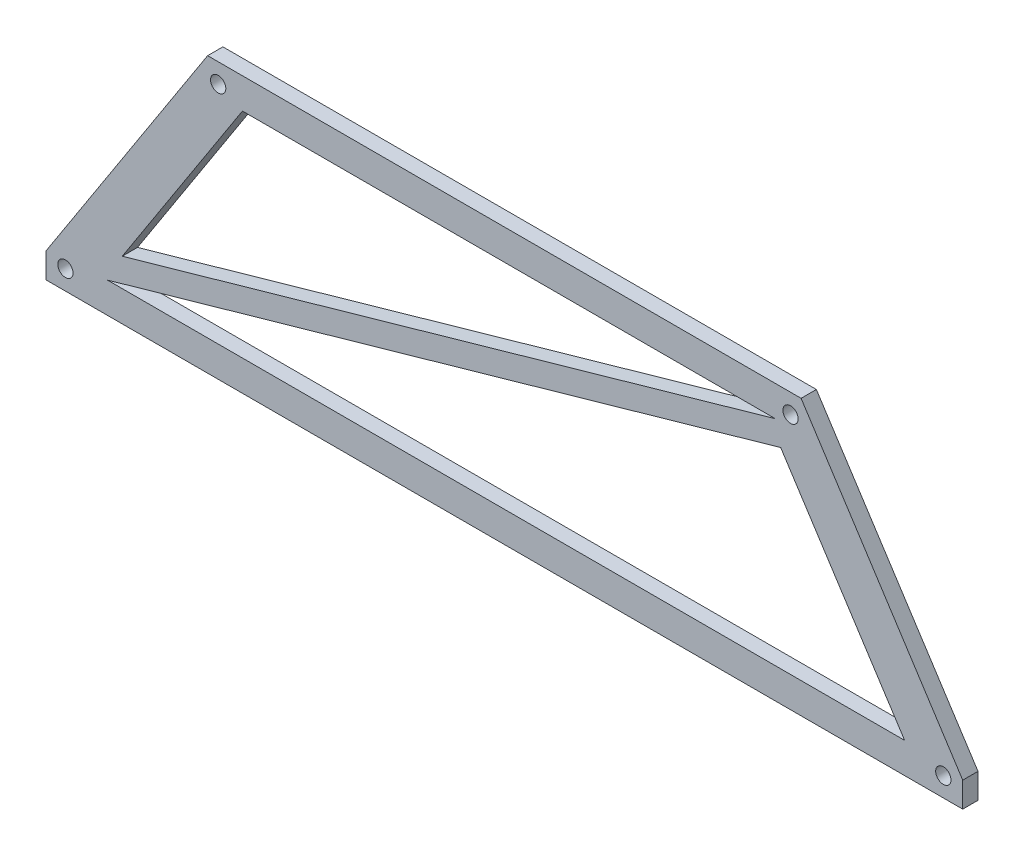
SolidWorks part; units mm, degrees
ref_plane "Front Plane" through (0, 0, 0) normal (0, 0, 1) x (1, 0, 0)
ref_plane "Top Plane" through (0, 0, 0) normal (0, 1, 0) x (1, 0, 0)
ref_plane "Right Plane" through (0, 0, 0) normal (1, 0, 0) x (0, 0, -1)
sketch "Sketch1" plane through (0, 0, 0) normal (0, 0, 1) x (1, 0, 0)
  line L2 (300, -109.2652) -> (300, -92.8158)
  line L3 (194.2105, 70.7348) -> (-194.2105, 70.7348)
  line L4 (-300, -109.2652) -> (-300, -92.8158)
  line L5 (300, -109.2652) -> (-194.2105, 70.7348) construction
  line L6 (194.2105, 70.7348) -> (-300, -109.2652) construction
  line L9 (300, -109.2652) -> (-300, -109.2652)
  line L10 (0, -55) -> (0, 55) construction
  line L11 (-194.2105, 70.7348) -> (-300, -92.8158)
  line L12 (194.2105, 70.7348) -> (300, -92.8158)
  circle A0 centre (-187.3, 58.0348) radius 5
  circle A1 centre (-287.3, -96.5652) radius 5
  circle A2 centre (287.3, -96.5652) radius 5
  circle A3 centre (187.3, 58.0348) radius 5
  point P0 (0, 0)
  dimension "D7" = 10
  dimension "D2" = 12.7
  dimension "D3" = 12.7
  dimension "D4" = 600
  dimension "D5" = 12.7
  dimension "D8" = 112.7
  dimension "D9" = 154.6
  dimension "D10" = 12.7
  dimension "D11" = 12.7
extrude "Boss-Extrude1" add sketch "Sketch1" along normal blind 10
sketch "Sketch2" plane through (0, 0, 10) normal (0, 0, 1) x (1, 0, 0)
  line L0 (180.8634, 36.1325) -> (261.9745, -89.2652)
  line L1 (261.9745, -89.2652) -> (-259.82, -89.2652)
  line L2 (-259.82, -89.2652) -> (180.8634, 36.1325)
  line L3 (-300, -109.2652) -> (300, -109.2652) construction
  line L4 (300, -92.8158) -> (194.2105, 70.7348) construction
  line L5 (-250.0973, -70.9031) -> (177.373, 50.7348)
  line L6 (177.373, 50.7348) -> (-171.4182, 50.7348)
  line L7 (-171.4182, 50.7348) -> (-250.0973, -70.9031)
  line L8 (-194.2105, 70.7348) -> (-300, -92.8158) construction
  line L9 (194.2105, 70.7348) -> (-194.2105, 70.7348) construction
  point P14 (-250.4467, -71.4433)
  point P15 (175.3426, 53.0348)
  point P16 (0, 0)
  dimension "D1" = 30
  dimension "D2" = 30
  dimension "D3" = 15
  dimension "D4" = 20
  dimension "D5" = 521.7945
  dimension "D6" = 20
  dimension "D7" = 25
extrude "Cut-Extrude1" cut sketch "Sketch2" against normal through all
